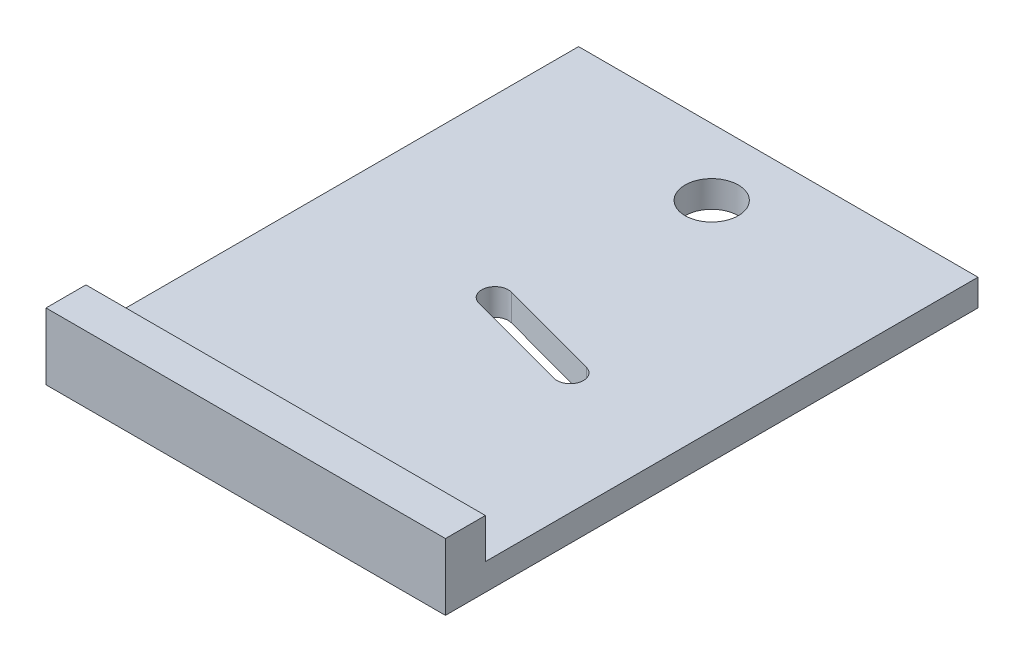
SolidWorks part; units mm, degrees
material "6061-T6 (SS)"
ref_plane "Front Plane" through (0, 0, 0) normal (0, 0, 1) x (1, 0, 0)
ref_plane "Top Plane" through (0, 0, 0) normal (0, 1, 0) x (1, 0, 0)
ref_plane "Right Plane" through (0, 0, 0) normal (1, 0, 0) x (0, 0, -1)
sketch "Sketch1" plane through (0, 0, 0) normal (0, 1, 0) x (1, 0, 0)
  line L1 (0, 0) -> (60, 0)
  line L2 (0, 0) -> (0, 80)
  line L3 (0, 80) -> (60, 80)
  line L4 (60, 0) -> (60, 80)
  dimension "D1" = 60
  dimension "D2" = 80
extrude "Boss-Extrude1" add sketch "Sketch1" along normal blind 4
sketch "Sketch2" plane through (0, 0, 0) normal (0, 0, 1) x (1, 0, 0)
  line L0 (60, 4) -> (60, 0) construction
  line L1 (0, 0) -> (60, 0)
  line L2 (0, 0) -> (0, 10)
  line L3 (0, 10) -> (60, 10)
  line L4 (60, 0) -> (60, 10)
  dimension "D1" = 10
extrude "Boss-Extrude2" add sketch "Sketch2" against normal blind 6
hole_wizard "Ø8.0mm Dowel Hole1" positions "Sketch5" profile "Sketch4" hole size "Ø8.0" standard "DIN"
sketch "Sketch5" plane through (0, 4, 0) normal (0, 1, 0) x (1, 0, 0)
  line L0 (30, 80) -> (30, -12.0374) construction
  line L1 (60, 80) -> (0, 80) construction
  point P6 (30, 70)
  dimension "D1" = 10
sketch "Sketch4" plane through (30, 4, -70) normal (1, 0, 0) x (0, 0, 1)
  line L0 (0, 0) -> (0, 6)
  line L1 (0, 6) -> (4, 6)
  line L2 (4, 6) -> (4, 0)
  line L5 (4, 0) -> (0, 0)
  line L10 (0, 6) -> (-4, 6) construction
  line L11 (0, -6.35) -> (0, 107.95) construction
  dimension "Hole Dia." = 8
  dimension "Hole Depth" = 6
  dimension "Drill Angle" = 180
sketch "Sketch6" plane through (0, 0, 0) normal (0, -1, 0) x (1, 0, 0)
  line L0 (41.5879, -66.8822) -> (26.5879, -11.1322) construction
  line L1 (41.5879, -66.8822) -> (26.5879, -11.1322) construction
  line L2 (26.3626, -41.0857) -> (41.8132, -36.9286) construction
  line L3 (26.3626, -41.0857) -> (41.8132, -36.9286) construction
  line L4 (25.843, -39.1544) -> (41.2935, -34.9973)
  line L5 (26.8823, -43.017) -> (42.3328, -38.86)
  arc A0 (25.843, -39.1544) -> (26.8823, -43.017) centre (26.3626, -41.0857) ccw
  arc A1 (42.3328, -38.86) -> (41.2935, -34.9973) centre (41.8132, -36.9286) ccw
  point P4 (34.0879, -39.0072)
  point P5 (34.0879, -39.0072)
  dimension "D1" = 2
  dimension "D2" = 16
extrude "Cut-Extrude1" cut sketch "Sketch6" against normal through all
